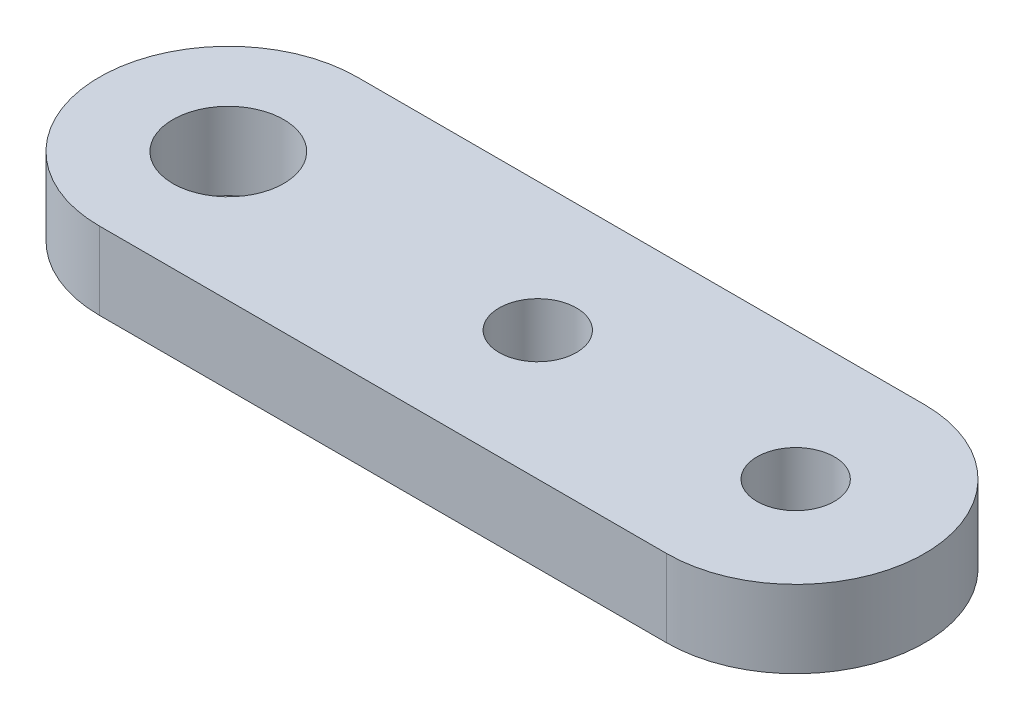
SolidWorks part; units mm, degrees
material "Thornel Mat VMA"
ref_plane "前视基准面" through (0, 0, 0) normal (0, 0, 1) x (1, 0, 0)
ref_plane "上视基准面" through (0, 0, 0) normal (0, 1, 0) x (1, 0, 0)
ref_plane "右视基准面" through (0, 0, 0) normal (1, 0, 0) x (0, 0, -1)
sketch "草图1" plane through (0, 0, 0) normal (0, 1, 0) x (1, 0, 0)
  line L0 (-22, 0) -> (0, 0) construction
  line L1 (-22, 5) -> (0, 5)
  line L2 (-22, -5) -> (0, -5)
  circle A0 centre (0, 0) radius 1.5
  circle A1 centre (-10, 0) radius 1.5
  circle A2 centre (-22, 0) radius 2.15
  arc A3 (-22, 5) -> (-22, -5) centre (-22, 0) ccw
  arc A4 (0, -5) -> (0, 5) centre (0, 0) ccw
  point P7 (-11, 0)
  dimension "D1" = 3
  dimension "D2" = 10
  dimension "D3" = 4.3
  dimension "D4" = 10
  dimension "D5" = 22
extrude "凸台-拉伸1" add sketch "草图1" along normal blind 3
